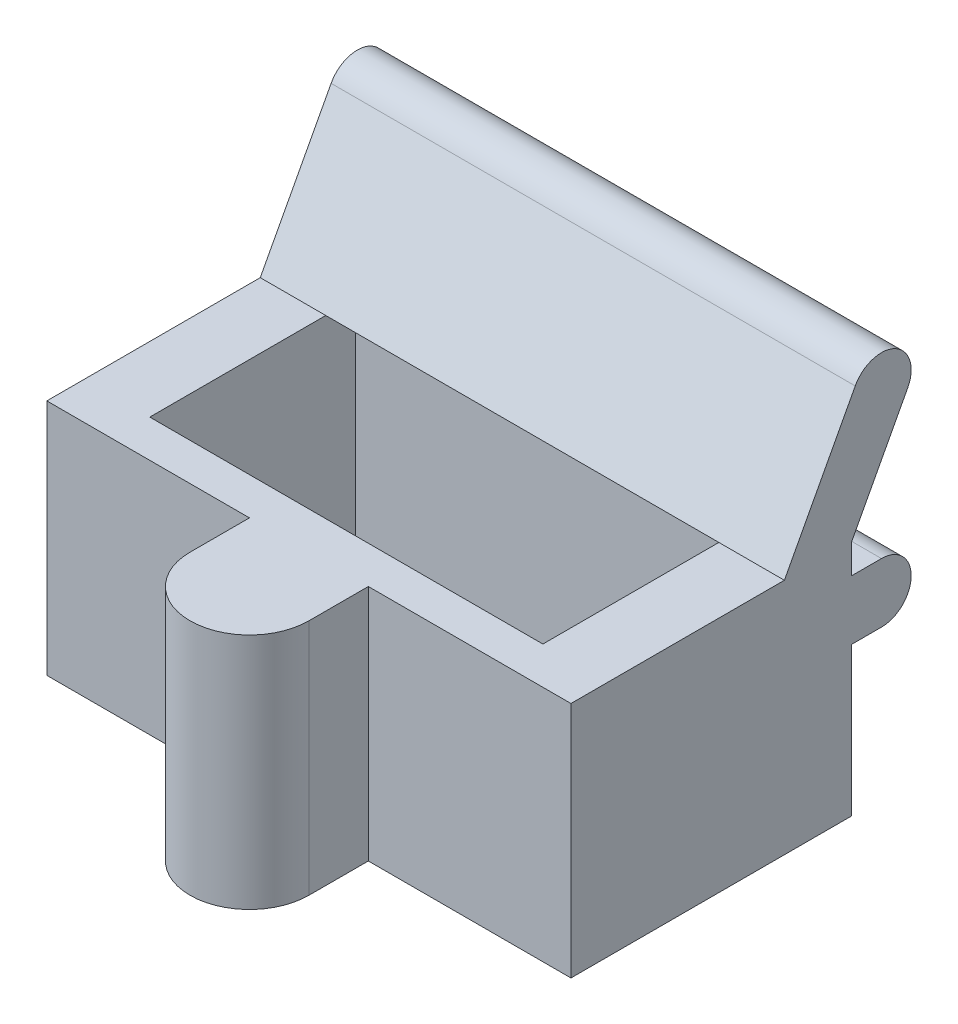
SolidWorks part; units mm, degrees
ref_plane "Front Plane" through (0, 0, 0) normal (0, 0, 1) x (1, 0, 0)
ref_plane "Top Plane" through (0, 0, 0) normal (0, 1, 0) x (1, 0, 0)
ref_plane "Right Plane" through (0, 0, 0) normal (1, 0, 0) x (0, 0, -1)
sketch "Sketch1" plane through (0, 0, 0) normal (0, 1, 0) x (1, 0, 0)
  line L1 (-28, 15) -> (28, 15)
  line L2 (-28, 15) -> (-28, -15)
  line L3 (-28, -15) -> (28, -15)
  line L4 (28, 15) -> (28, -15)
  line L5 (-28, 15) -> (28, -15) construction
  line L6 (-28, -15) -> (28, 15) construction
  line L7 (-21, 11) -> (21, 11)
  line L8 (-21, 11) -> (-21, -11)
  line L9 (-21, -11) -> (21, -11)
  line L10 (21, 11) -> (21, -11)
  line L11 (-21, 11) -> (21, -11) construction
  line L12 (-21, -11) -> (21, 11) construction
  point P0 (0, 0)
  point P5 (0, 0)
  dimension "D1" = 56
  dimension "D2" = 30
  dimension "D3" = 42
  dimension "D4" = 22
extrude "Boss-Extrude1" add sketch "Sketch1" along normal blind 25.4 contours L4 L1 L2 L3 L7 L10 L9 L8
sketch "Sketch2" plane through (28, 0, 0) normal (1, 0, 0) x (0, 0, -1)
  line L0 (15, 25.4) -> (15, 0) construction
  line L1 (18.175, 22.225) -> (15, 22.225)
  line L2 (18.175, 15.875) -> (15, 15.875)
  line L3 (15, 22.225) -> (15, 15.875)
  line L4 (15, 25.4) -> (-15, 25.4) construction
  arc A0 (18.175, 15.875) -> (18.175, 22.225) centre (18.175, 19.05) ccw
  dimension "D1" = 6.35
  dimension "D2" = 6.35
extrude "Boss-Extrude2" add sketch "Sketch2" against normal up to surface (56 mm away) up to face at (-28, 12.7, 0)
sketch "Sketch3" plane through (28, 0, 0) normal (1, 0, 0) x (0, 0, -1)
  line L0 (18.175, 19.05) -> (18.175, 38.1) construction
  line L1 (15, 25.4) -> (20.9765, 36.6059)
  line L2 (15.3735, 39.5941) -> (7.8033, 25.4)
  line L3 (15, 25.4) -> (-15, 25.4) construction
  line L4 (7.8033, 25.4) -> (15, 25.4)
  arc A0 (20.9765, 36.6059) -> (15.3735, 39.5941) centre (18.175, 38.1) ccw
  dimension "D1" = 6.35
  dimension "D2" = 19.05
extrude "Boss-Extrude3" add sketch "Sketch3" against normal up to surface (56 mm away) up to face at (-28, 15.875, -8.6906)
sketch "Sketch4" plane through (0, 0, 0) normal (0, -1, 0) x (1, 0, 0)
  line L0 (-28, 15) -> (28, 15) construction
  line L1 (-6.35, 21.35) -> (-6.35, 15)
  line L2 (6.35, 21.35) -> (6.35, 15)
  line L3 (-6.35, 15) -> (6.35, 15)
  arc A0 (6.35, 21.35) -> (-6.35, 21.35) centre (0, 21.35) ccw
  dimension "D1" = 12.7
extrude "Boss-Extrude4" add sketch "Sketch4" against normal up to surface (25.4 mm away) up to face at (0, 25.4, 2.5983)
